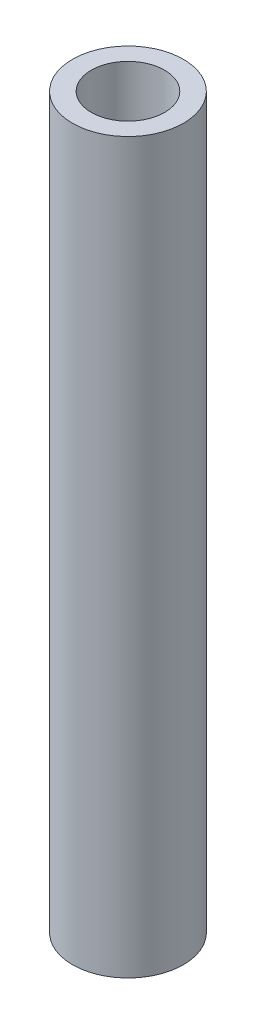
SolidWorks part; units mm, degrees
material "ABS"
ref_plane "Front Plane" through (0, 0, 0) normal (0, 0, 1) x (1, 0, 0)
ref_plane "Top Plane" through (0, 0, 0) normal (0, 1, 0) x (1, 0, 0)
ref_plane "Right Plane" through (0, 0, 0) normal (1, 0, 0) x (0, 0, -1)
sketch "Sketch1" plane through (0, 0, 0) normal (0, 1, 0) x (1, 0, 0)
  circle A0 centre (0, 0) radius 4.425
  circle A1 centre (0, 0) radius 2.925
  dimension "D1" = 8.85
  dimension "D2" = 1.5
extrude "Boss-Extrude1" add sketch "Sketch1" against normal up to surface (58.15 mm away)
